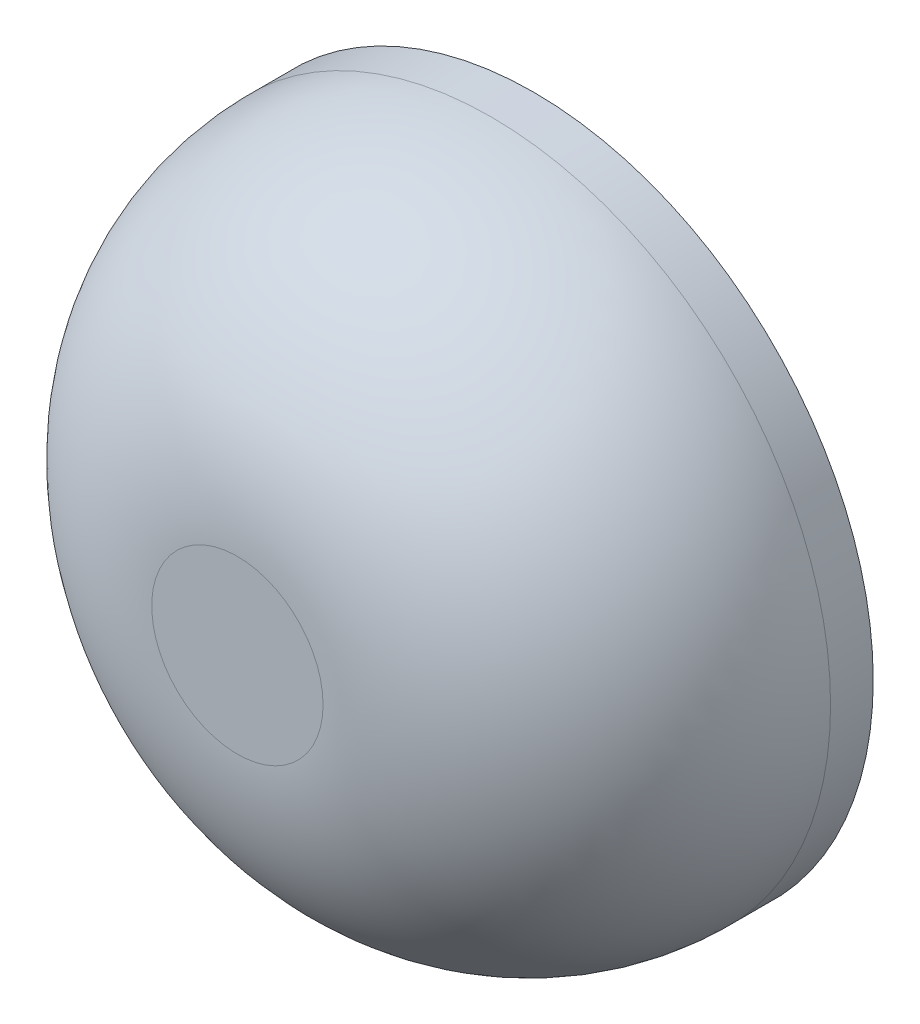
SolidWorks part; units mm, degrees
material "ABS"
ref_plane "Front Plane" through (0, 0, 0) normal (0, 0, 1) x (1, 0, 0)
ref_plane "Top Plane" through (0, 0, 0) normal (0, 1, 0) x (1, 0, 0)
ref_plane "Right Plane" through (0, 0, 0) normal (1, 0, 0) x (0, 0, -1)
sketch "Sketch1" plane through (0, 0, 0) normal (0, 0, 1) x (1, 0, 0)
  circle A0 centre (0, 0) radius 69.85
  dimension "D1" = 139.7
extrude "Boss-Extrude1" add sketch "Sketch1" along normal blind 61
fillet "Fillet1" radius 52.22 1 edges at (69.85, 0, 61)
